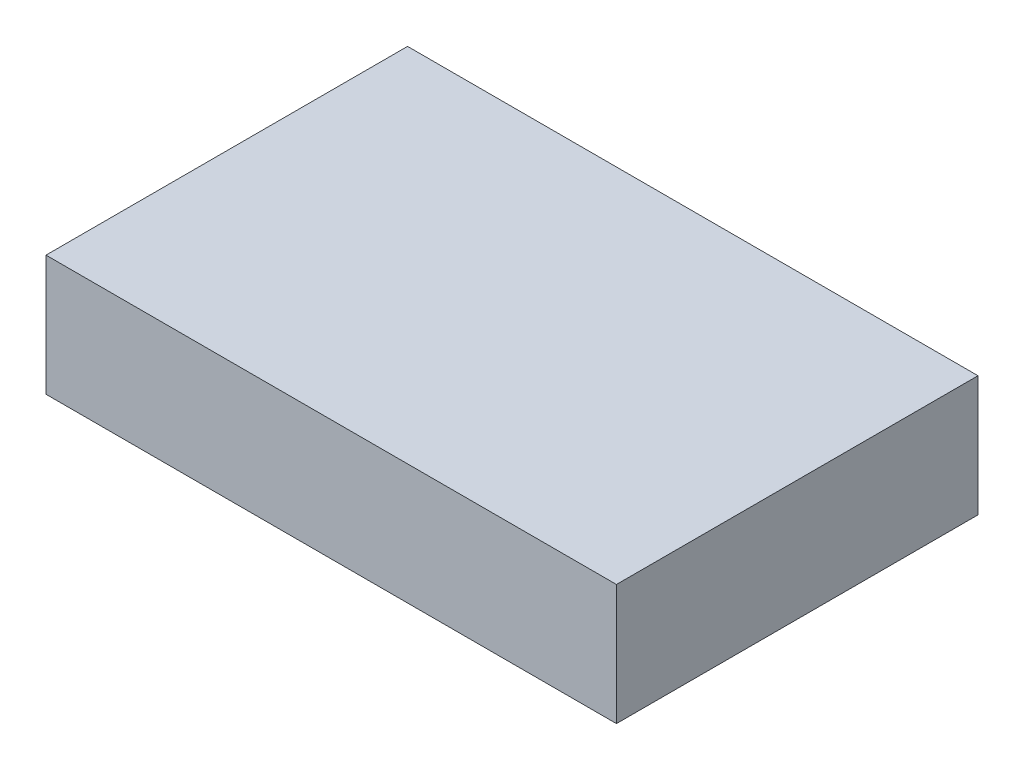
SolidWorks part; units mm, degrees
ref_plane "前视基准面" through (0, 0, 0) normal (0, 0, 1) x (1, 0, 0)
ref_plane "上视基准面" through (0, 0, 0) normal (0, 1, 0) x (1, 0, 0)
ref_plane "右视基准面" through (0, 0, 0) normal (1, 0, 0) x (0, 0, -1)
other "Configuration Table"
sketch "草图1" plane through (0, 0, 0) normal (0, 1, 0) x (1, 0, 0)
  line L1 (0, 0) -> (71, 0)
  line L2 (0, 0) -> (0, 45)
  line L3 (0, 45) -> (71, 45)
  line L4 (71, 0) -> (71, 45)
  dimension "D1" = 71
  dimension "D2" = 45
extrude "凸台-拉伸1" add sketch "草图1" along normal blind 15
